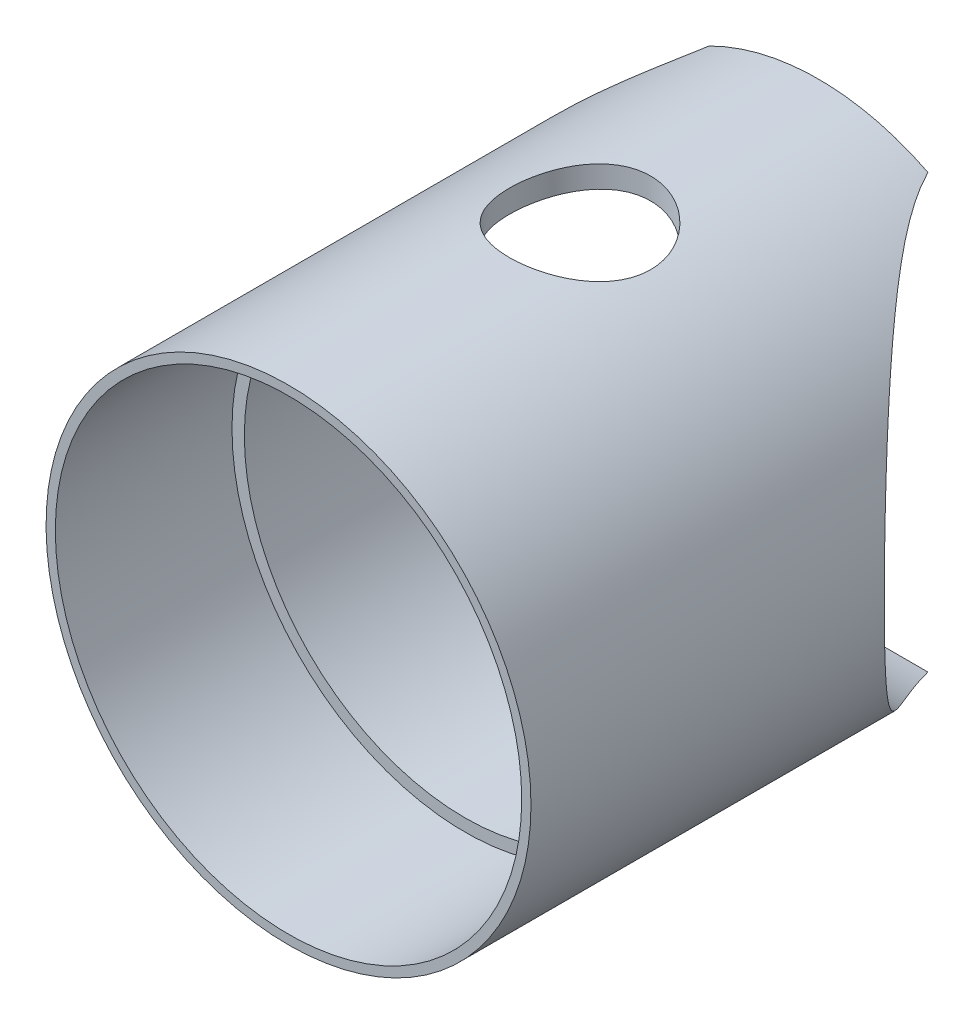
SolidWorks part; units mm, degrees
material "6061-T6 (SS)"
ref_plane "Front Plane" through (0, 0, 0) normal (0, 0, 1) x (1, 0, 0)
ref_plane "Top Plane" through (0, 0, 0) normal (0, 1, 0) x (1, 0, 0)
ref_plane "Right Plane" through (0, 0, 0) normal (1, 0, 0) x (0, 0, -1)
sketch "Sketch2" plane through (0, 0, 0) normal (0, 0, 1) x (1, 0, 0)
  circle A0 centre (0, 0) radius 33.528
  circle A1 centre (0, 0) radius 34.8615
  dimension "D1" = 67.056
  dimension "D2" = 1.3335
extrude "Boss-Extrude1" add sketch "Sketch2" along normal blind 25.4
sketch "Sketch3" plane through (0, 0, 0) normal (0, 0, -1) x (-1, 0, 0)
  circle A0 centre (0, 0) radius 34.8615
  dimension "D1" = 69.723
extrude "Boss-Extrude2" add sketch "Sketch3" along normal blind 50.8
ref_plane "Plane1" through (34.8615, 0, 0) normal (1, 0, 0) x (0, 0, -1)
sketch "Sketch4" plane through (34.8615, 0, 0) normal (1, 0, 0) x (0, 0, -1)
  circle A0 centre (57.15, 0) radius 31.75
  dimension "D1" = 63.5
  dimension "D2" = 57.15
extrude "Cut-Extrude2" cut sketch "Sketch4" against normal through all
sketch "Sketch6" plane through (0, 0, 0) normal (0, 0, 1) x (1, 0, 0)
  circle A0 centre (0, 0) radius 31.75
  dimension "D1" = 63.5
extrude "Cut-Extrude4" cut sketch "Sketch6" against normal blind 50.8
ref_plane "Plane2" through (0, 34.8615, 0) normal (0, 1, 0) x (-1, 0, 0)
sketch "Sketch7" plane through (0, 34.8615, 0) normal (0, 1, 0) x (-1, 0, 0)
  line L0 (34.8615, 25.4) -> (-34.8615, 25.4) construction
  circle A0 centre (0, -16.51) radius 10.16
  dimension "D1" = 20.32
  dimension "D2" = 41.91
extrude "Cut-Extrude5" cut sketch "Sketch7" against normal up to next
